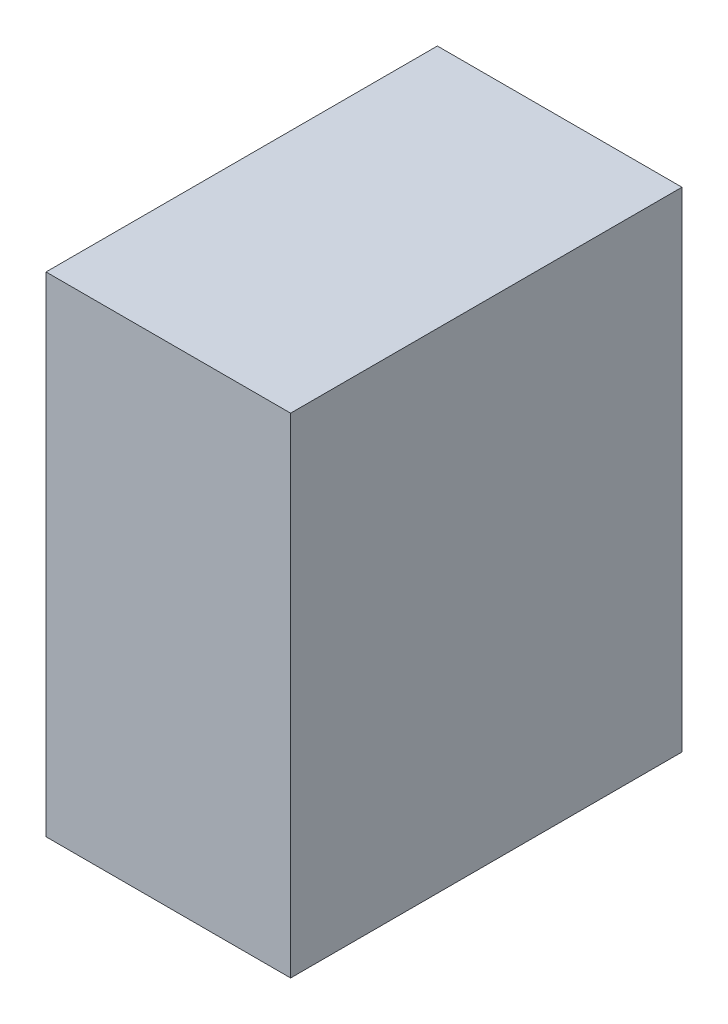
SolidWorks part; units mm, degrees
ref_plane "Front Plane" through (0, 0, 0) normal (0, 0, 1) x (1, 0, 0)
ref_plane "Top Plane" through (0, 0, 0) normal (0, 1, 0) x (1, 0, 0)
ref_plane "Right Plane" through (0, 0, 0) normal (1, 0, 0) x (0, 0, -1)
sketch "Sketch1" plane through (0, 0, 0) normal (0, 0, 1) x (1, 0, 0)
  line L1 (0, 0) -> (0.25, 0)
  line L2 (0, 0) -> (0, 0.5)
  line L3 (0, 0.5) -> (0.25, 0.5)
  line L4 (0.25, 0) -> (0.25, 0.5)
  dimension "D1" = 0.25
  dimension "D2" = 0.5
extrude "Boss-Extrude1" add sketch "Sketch1" along normal blind 0.4 contours L2 L3 L4 L1
equation "\"t\"= 0.25'thickness of the sheets"
equation "\"t_cf\" = 0.115'thickness of single carbon fiber layer"
equation "\"t_kapton\" = 0.025'thickness of single Kapton flex layer"
equation "\"t_fr4\" = 0.1'thickness of FR4 with copper layer"
equation "\"joint_flex\"= 0.1'Width of flextures gap"
equation "\"joint_flex_eff\"= 0.02'Width of flecture after castelation"
equation "\"joint_fold\"= 0.2'Width of folding joints for 90deg fold"
equation "\"gap_tolerance\"= 0.002'Width to have interfecence fit between carbon fiber inserts"
equation "\"assemble_angle\"= 90'Angle of assembly parts"
equation "\"link_lift\"= 0.5'Actuation linkage amplification for the lift motion"
equation "\"link_swing\"= 0.45'Actuation linkage amplification for the swing motion"
equation "\"D1@Sketch1\"=\"t\""
equation "\"D1@Boss-Extrude1\"=\"joint_fold\"*2"
